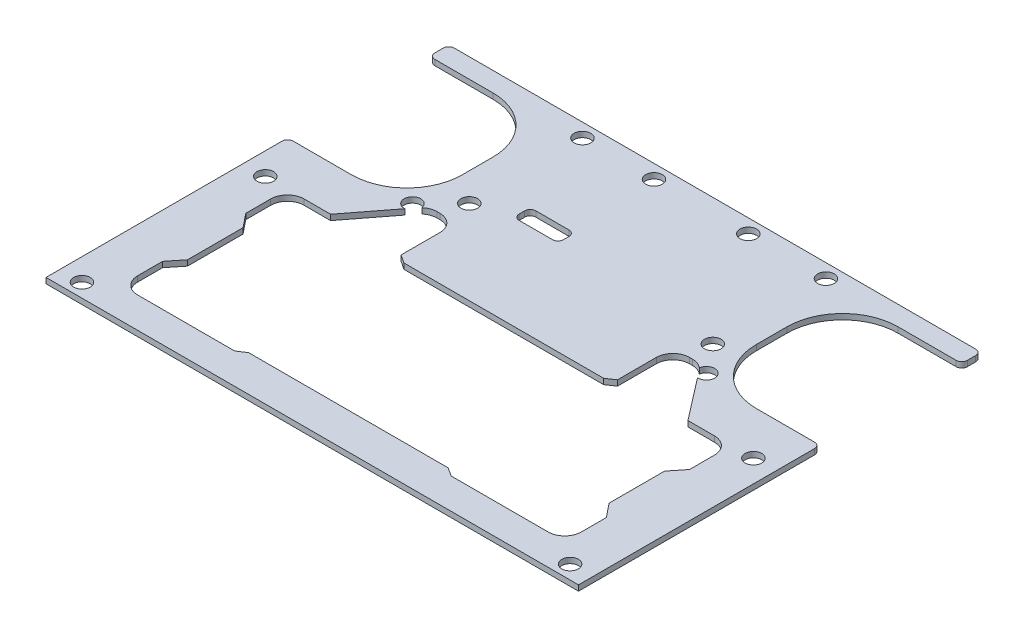
SolidWorks part; units mm, degrees
ref_plane "Спереди" through (0, 0, 0) normal (0, 0, 1) x (1, 0, 0)
ref_plane "Сверху" through (0, 0, 0) normal (0, 1, 0) x (1, 0, 0)
ref_plane "Справа" through (0, 0, 0) normal (1, 0, 0) x (0, 0, -1)
sketch "Эскиз1" plane through (0, 0, 0) normal (0, 1, 0) x (1, 0, 0)
  line L0 (-48, -36.305) -> (48, -36.305)
  line L3 (-48, -36.305) -> (-48, 6.2547)
  line L4 (-47, 36.305) -> (47, 36.305)
  line L7 (-19.5, -0.7872) -> (-18, -1.7872)
  line L8 (-18, -1.7872) -> (18, -1.7872)
  line L9 (18, -1.7872) -> (19.5, -0.7872)
  line L11 (40, -3.7872) -> (40, -8.2872)
  line L12 (40, -8.2872) -> (38, -10.7872)
  line L13 (38, -10.7872) -> (38, -20.7872)
  line L14 (38, -20.7872) -> (40, -23.2872)
  line L15 (40, -23.2872) -> (40, -27.7872)
  line L16 (37, -30.7872) -> (19.5, -30.7872)
  line L17 (19.5, -30.7872) -> (18, -29.7872)
  line L18 (18, -29.7872) -> (-18, -29.7872)
  line L19 (-18, -29.7872) -> (-19.5, -30.7872)
  line L20 (-37, -30.7872) -> (-19.5, -30.7872)
  line L21 (-47, 32.7884) -> (-36.5, 32.7884)
  line L22 (-40, -27.7872) -> (-40, -23.2872)
  line L23 (-40, -23.2872) -> (-38, -20.7872)
  line L24 (-38, -20.7872) -> (-38, -10.7872)
  line L25 (-38, -10.7872) -> (-40, -8.2872)
  line L26 (-40, -8.2872) -> (-40, -3.7872)
  line L27 (-26.5, 17.2547) -> (-26.5, 22.7884)
  line L28 (-47, 7.2547) -> (-36.5, 7.2547)
  line L29 (-19.5, -0.7872) -> (-19.5, 6.2128)
  line L30 (0, 36.305) -> (0, 0) construction
  line L31 (-48, 33.7884) -> (-48, 35.305)
  line L32 (48, 33.7884) -> (48, 35.305)
  line L33 (47, 7.2547) -> (36.5, 7.2547)
  line L34 (26.5, 17.2547) -> (26.5, 22.7884)
  line L35 (47, 32.7884) -> (36.5, 32.7884)
  line L36 (48, -36.305) -> (48, 6.2547)
  line L38 (-23.0245, 9.2128) -> (-22.5, 9.2128)
  line L42 (-37, -0.7872) -> (-32.2069, -0.7872)
  line L43 (-25.4007, 8.0441) -> (-32.2069, -0.7872)
  line L44 (19.5, -0.7872) -> (19.5, 6.2128)
  line L45 (23.0245, 9.2128) -> (22.5, 9.2128)
  line L46 (25.4007, 8.0441) -> (32.2069, -0.7872)
  line L47 (37, -0.7872) -> (32.2069, -0.7872)
  arc A0 (40, -3.7872) -> (37, -0.7872) centre (37, -3.7872) ccw construction
  arc A1 (-40, -3.7872) -> (-37, -0.7872) centre (-37, -3.7872) cw
  arc A2 (-40, -27.7872) -> (-37, -30.7872) centre (-37, -27.7872) ccw
  arc A3 (37, -30.7872) -> (40, -27.7872) centre (37, -27.7872) ccw
  arc A4 (37, -0.7872) -> (40, -3.7872) centre (37, -3.7872) cw
  arc A5 (-36.5, 7.2547) -> (-26.5, 17.2547) centre (-36.5, 17.2547) ccw
  arc A6 (-36.5, 32.7884) -> (-26.5, 22.7884) centre (-36.5, 22.7884) cw
  arc A7 (-48, 35.305) -> (-47, 36.305) centre (-47, 35.305) cw
  arc A8 (-48, 33.7884) -> (-47, 32.7884) centre (-47, 33.7884) ccw
  arc A9 (-48, 6.2547) -> (-47, 7.2547) centre (-47, 6.2547) cw
  arc A10 (48, 6.2547) -> (47, 7.2547) centre (47, 6.2547) ccw
  arc A11 (48, 33.7884) -> (47, 32.7884) centre (47, 33.7884) cw
  arc A12 (48, 35.305) -> (47, 36.305) centre (47, 35.305) ccw
  arc A13 (36.5, 32.7884) -> (26.5, 22.7884) centre (36.5, 22.7884) ccw
  arc A14 (36.5, 7.2547) -> (26.5, 17.2547) centre (36.5, 17.2547) cw
  circle A15 centre (-21.3971, 13.405) radius 1.5
  circle A16 centre (-21.3971, 33.805) radius 1.5
  circle A17 centre (22.5029, 13.405) radius 1.5
  circle A18 centre (22.5029, 33.805) radius 1.5
  arc A20 (-19.5, 6.2128) -> (-22.5, 9.2128) centre (-22.5, 6.2128) ccw
  arc A23 (-23.0245, 9.2128) -> (-25.4007, 8.0441) centre (-23.0245, 6.2128) ccw
  arc A24 (19.5, 6.2128) -> (22.5, 9.2128) centre (22.5, 6.2128) cw
  arc A25 (23.0245, 9.2128) -> (25.4007, 8.0441) centre (23.0245, 6.2128) cw
  point P75 (-48, 36.305)
  point P78 (-48, 32.7884)
  point P81 (-48, 7.2547)
  point P97 (48, 7.2547)
  point P98 (48, 32.7884)
  point P99 (48, 36.305)
  point P112 (-19.5, 9.2128)
  point P119 (-24.5, 9.2128)
  dimension "D3" = 10
  dimension "D1" = 1
  dimension "D4" = 1
  dimension "D6" = 3
  dimension "D7" = 3
  dimension "D2" = 72.6099
  dimension "D5" = 10
extrude "Бобышка-Вытянуть1" add sketch "Эскиз1" along normal blind 1
sketch "Эскиз3" plane through (0, 0, 0) normal (0, -1, 0) x (1, 0, 0)
  circle A0 centre (44, 33.8216) radius 1.5
  circle A1 centre (44, 0.7662) radius 1.5
  circle A2 centre (-44, 0.7662) radius 1.5
  circle A3 centre (-44, 33.8216) radius 1.5
extrude "Вырез-Вытянуть1" cut sketch "Эскиз3" against normal through all
sketch "Эскиз4" plane through (0, 0, 0) normal (0, -1, 0) x (1, 0, 0)
  circle A0 centre (-26.5, -8.2608) radius 1.5
  circle A1 centre (-8.5, -33.805) radius 1.5
  circle A2 centre (8.5, -33.805) radius 1.5
  circle A3 centre (26.5, -8.2608) radius 1.5
extrude "Вырез-Вытянуть2" cut sketch "Эскиз4" against normal through all
sketch "Эскиз6" plane through (0, 1, 0) normal (0, 1, 0) x (1, 0, 0)
  line L0 (-14.2473, 18.2456) -> (-8.2473, 18.2456)
  line L1 (-7.2473, 17.2456) -> (-7.2473, 16.2456)
  line L2 (-15.2473, 17.2456) -> (-15.2473, 16.2456)
  line L3 (-14.2473, 15.2456) -> (-8.2473, 15.2456)
  line L4 (-14.2473, 15.2456) -> (-8.2473, 15.2456) construction
  arc A0 (-8.2473, 15.2456) -> (-7.2473, 16.2456) centre (-8.2473, 16.2456) ccw construction
  arc A1 (-15.2473, 17.2456) -> (-14.2473, 18.2456) centre (-14.2473, 17.2456) cw
  arc A2 (-8.2473, 18.2456) -> (-7.2473, 17.2456) centre (-8.2473, 17.2456) cw
  arc A3 (-7.2473, 16.2456) -> (-8.2473, 15.2456) centre (-8.2473, 16.2456) cw
  arc A4 (-14.2473, 15.2456) -> (-15.2473, 16.2456) centre (-14.2473, 16.2456) cw
extrude "Вырез-Вытянуть3" cut sketch "Эскиз6" against normal through all
